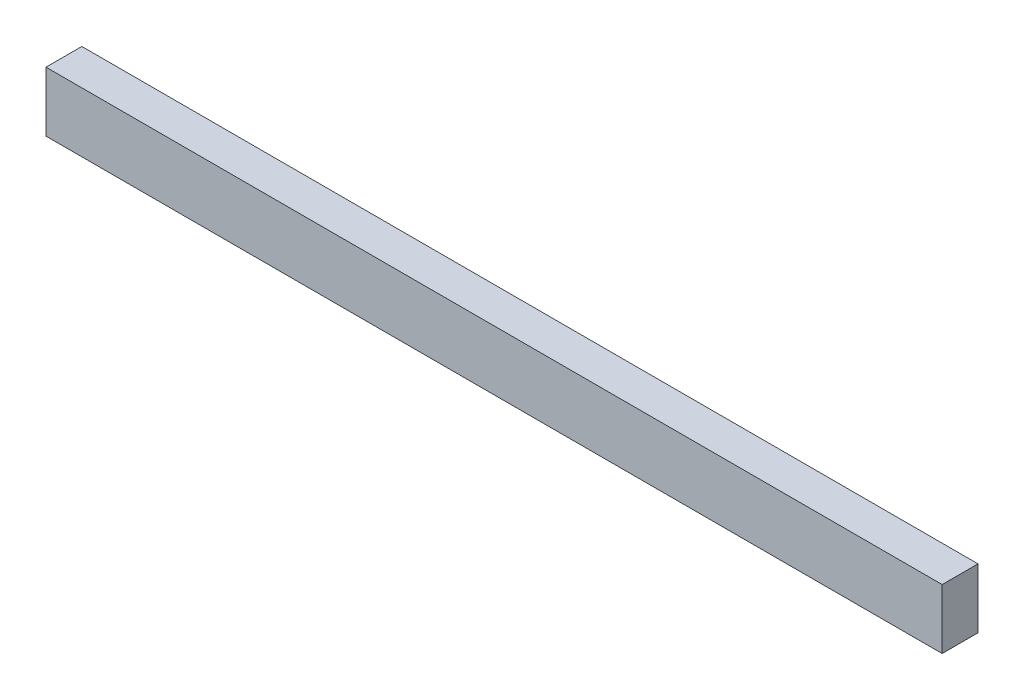
SolidWorks part; units mm, degrees
ref_plane "Front Plane" through (0, 0, 0) normal (0, 0, 1) x (1, 0, 0)
ref_plane "Top Plane" through (0, 0, 0) normal (0, 1, 0) x (1, 0, 0)
ref_plane "Right Plane" through (0, 0, 0) normal (1, 0, 0) x (0, 0, -1)
sketch "Sketch1" plane through (0, 0, 0) normal (0, 0, 1) x (1, 0, 0)
  line L1 (0, 0) -> (150, 0)
  line L2 (0, 0) -> (0, 10)
  line L3 (0, 10) -> (150, 10)
  line L4 (150, 0) -> (150, 10)
  dimension "D1" = 150
  dimension "D2" = 10
extrude "Boss-Extrude1" add sketch "Sketch1" along normal blind 6
